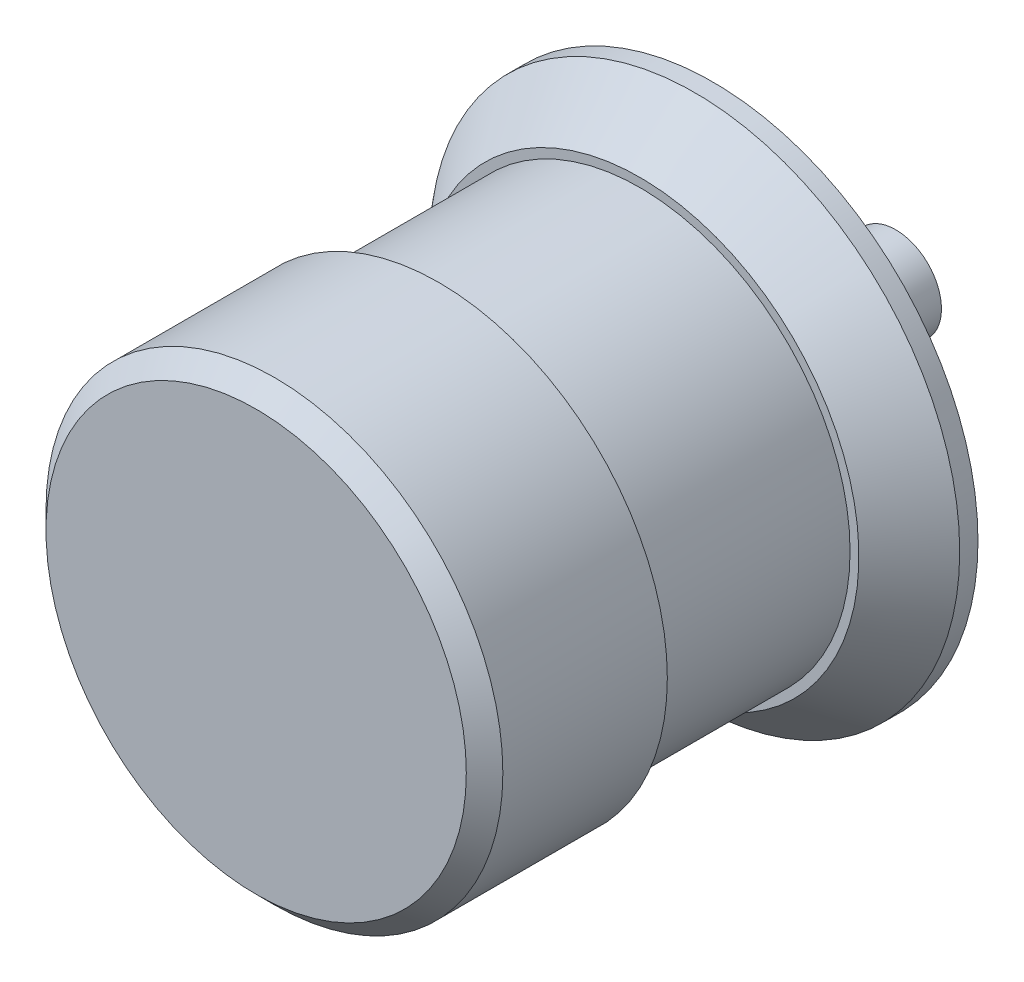
SolidWorks part; units mm, degrees
ref_plane "Front Plane" through (0, 0, 0) normal (0, 0, 1) x (1, 0, 0)
ref_plane "Top Plane" through (0, 0, 0) normal (0, 1, 0) x (1, 0, 0)
ref_plane "Right Plane" through (0, 0, 0) normal (1, 0, 0) x (0, 0, -1)
sketch "Sketch1" plane through (0, 0, 0) normal (0, 0, 1) x (1, 0, 0)
  circle A0 centre (0, 0) radius 29
  dimension "D1" = 58
extrude "Boss-Extrude1" add sketch "Sketch1" along normal blind 30
sketch "Sketch2" plane through (0, 0, 30) normal (0, 0, 1) x (1, 0, 0)
  circle A0 centre (0, 0) radius 23
  dimension "D1" = 46
extrude "Cut-Extrude1" cut sketch "Sketch2" against normal blind 22 flip side to cut
chamfer "Chamfer1" distance 6 angle 40 1 edges at (29, 0, 8)
sketch "Sketch3" plane through (0, 0, 30) normal (0, 0, 1) x (1, 0, 0)
  circle A0 centre (0, 0) radius 25
  dimension "D1" = 50
extrude "Boss-Extrude2" add sketch "Sketch3" along normal blind 20
sketch "Sketch4" plane through (0, 0, 0) normal (0, 0, -1) x (-1, 0, 0)
  circle A0 centre (0, 0) radius 5
  dimension "D1" = 10
extrude "Boss-Extrude3" add sketch "Sketch4" along normal blind 20
chamfer "Chamfer2" distance 2 angle 45 1 edges at (25, 0, 50)
